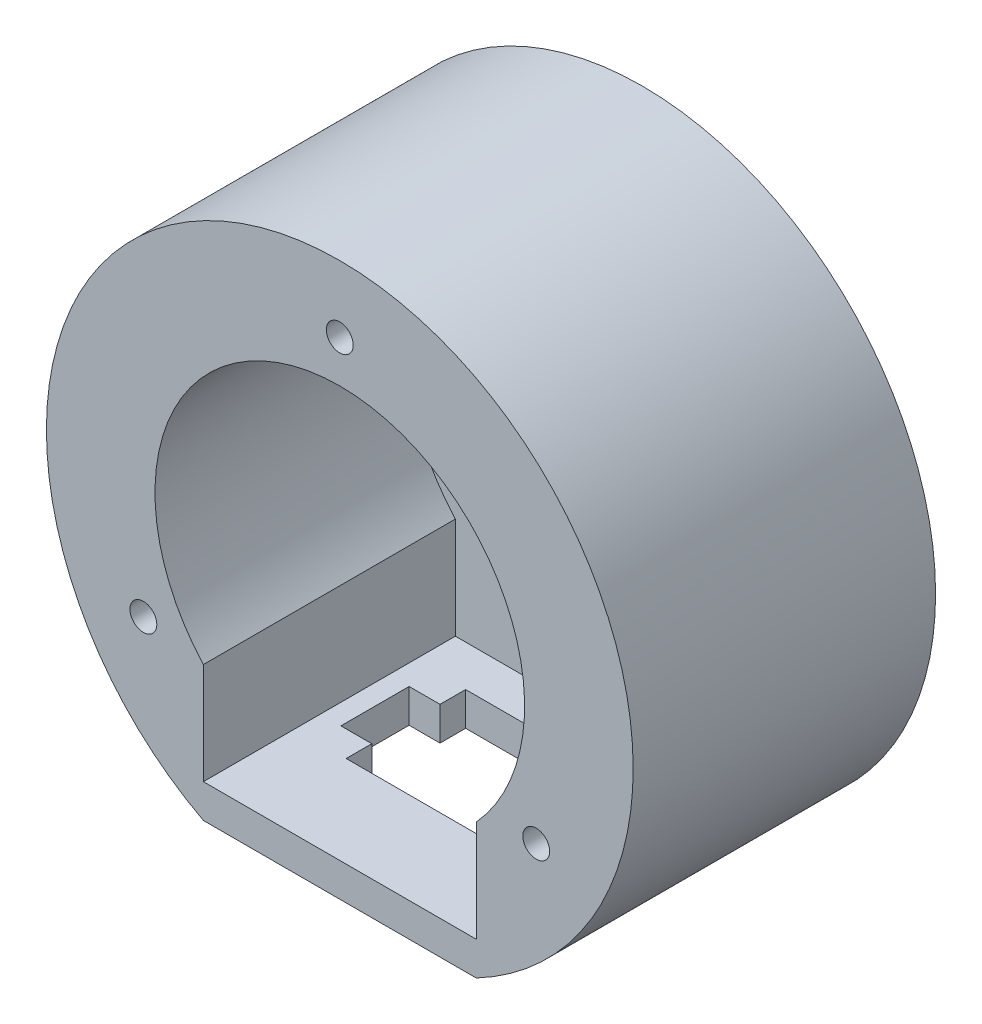
SolidWorks part; units mm, degrees
ref_plane "Front Plane" through (0, 0, 0) normal (0, 0, 1) x (1, 0, 0)
ref_plane "Top Plane" through (0, 0, 0) normal (0, 1, 0) x (1, 0, 0)
ref_plane "Right Plane" through (0, 0, 0) normal (1, 0, 0) x (0, 0, -1)
sketch "Sketch2" plane through (0, 0, 0) normal (0, 0, 1) x (1, 0, 0)
  circle A0 centre (0, 0) radius 17.4625
extrude "Boss-Extrude1" add sketch "Sketch2" along normal blind 18
sketch "Sketch13" plane through (0, 0, 18) normal (0, 0, 1) x (1, 0, 0)
  circle A0 centre (0, 13.5) radius 0.8
  circle A2 centre (11.6913, -6.75) radius 0.8
  circle A3 centre (-11.6913, -6.75) radius 0.8
  point P9 (0, 0)
  dimension "D1" = 3
  dimension "D2" = 13.5
extrude "Cut-Extrude6" cut sketch "Sketch13" against normal blind 10
sketch "Sketch16" plane through (0, 0, 18) normal (0, 0, 1) x (1, 0, 0)
  circle A0 centre (0, 0) radius 11
extrude "Cut-Extrude9" cut sketch "Sketch16" against normal blind 15
sketch "Sketch20" plane through (5.9573, 0, -11.0843) normal (0, 1, 0) x (0, 0, 1)
  line L0 (16.5293, -11.0218) -> (16.5293, -6.9068)
  line L1 (23.6393, -11.0218) -> (23.6393, -0.8118)
  line L2 (14.9293, -6.9068) -> (14.9293, -4.9268)
  line L3 (14.9293, -6.9068) -> (16.5293, -6.9068)
  line L4 (14.9293, -4.9268) -> (16.5293, -4.9268)
  line L5 (16.5293, -4.9268) -> (16.5293, -0.8118)
  line L6 (16.5293, -0.8118) -> (18.0543, -0.8118)
  line L7 (18.0543, -0.8118) -> (18.0543, 1.0282)
  line L8 (22.1143, -0.8118) -> (22.1143, 1.0282)
  line L9 (18.0543, 1.0282) -> (22.1143, 1.0282)
  line L10 (18.0543, -12.8618) -> (18.0543, -11.0218)
  line L11 (18.0543, -12.8618) -> (22.1143, -12.8618)
  line L12 (22.1143, -12.8618) -> (22.1143, -11.0218)
  line L13 (23.6393, -0.8118) -> (22.1143, -0.8118)
  line L14 (23.6393, -11.0218) -> (22.1143, -11.0218)
  line L15 (16.5293, -11.0218) -> (18.0543, -11.0218)
  line L16 (29.0843, -9.7935) -> (23.6393, -9.7935) construction
  line L18 (29.0843, -23.4198) -> (29.0843, 11.5052) construction
  line L19 (16.5293, -9.7935) -> (11.0843, -9.7935) construction
  line L20 (11.0843, 11.5052) -> (11.0843, -23.4198) construction
  dimension "D2" = 4.06
  dimension "D3" = 10.21
  dimension "D4" = 13.89
  dimension "D5" = 1.98
  dimension "D6" = 8.71
  dimension "D7" = 7.11
extrude "Cut-Extrude11" cut sketch "Sketch20" against normal blind 22
sketch "Sketch21" plane through (0, 0, 18) normal (0, 0, 1) x (1, 0, 0)
  line L1 (-8.125, -15.46) -> (8.125, -15.46)
  line L2 (-8.125, -15.46) -> (-8.125, -18.2444)
  line L3 (-8.125, -18.2444) -> (8.125, -18.2444)
  line L4 (8.125, -15.46) -> (8.125, -18.2444)
  dimension "D1" = 16.25
  dimension "D2" = 8.125
  dimension "D3" = 15.46
extrude "Cut-Extrude12" cut sketch "Sketch21" against normal through all
sketch "Sketch24" plane through (0, 0, 18) normal (0, 0, 1) x (1, 0, 0)
  line L0 (-8.1196, -6.7586) -> (8.1304, -6.7586)
  line L1 (-8.1196, -6.7586) -> (-8.1196, -13.46)
  line L2 (-8.1196, -13.46) -> (8.1304, -13.46)
  line L3 (8.1304, -6.7586) -> (8.1304, -13.46)
  dimension "D1" = 16.25
extrude "Cut-Extrude13" cut sketch "Sketch24" against normal up to surface (15 mm away) up to face at (11, 0, 3)
